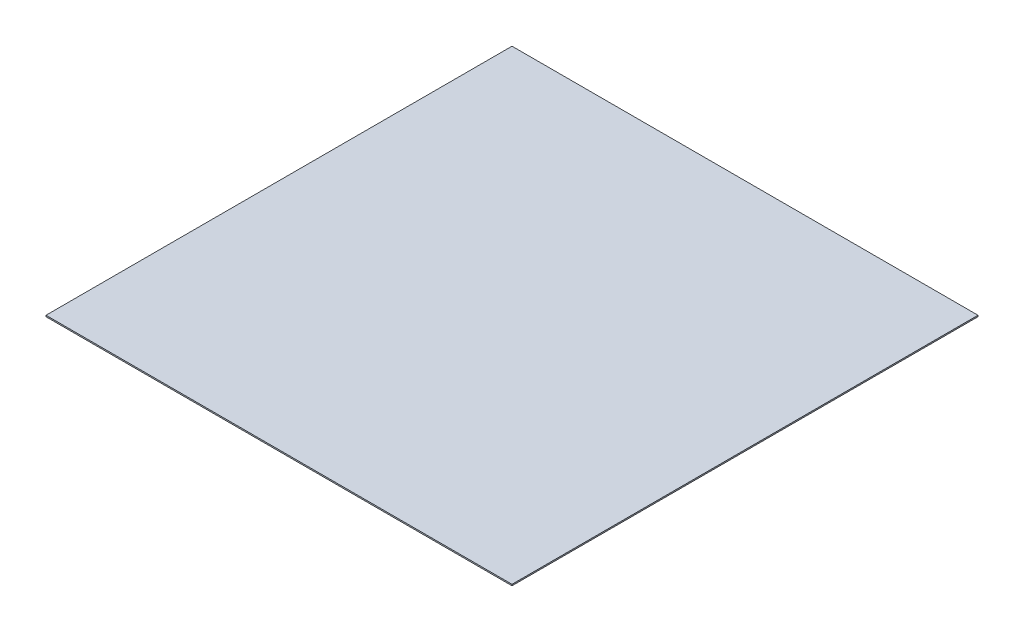
SolidWorks part; units mm, degrees
ref_plane "Front Plane" through (0, 0, 0) normal (0, 0, 1) x (1, 0, 0)
ref_plane "Top Plane" through (0, 0, 0) normal (0, 1, 0) x (1, 0, 0)
ref_plane "Right Plane" through (0, 0, 0) normal (1, 0, 0) x (0, 0, -1)
sketch "Sketch1" plane through (0, 0, 0) normal (0, 1, 0) x (1, 0, 0)
  line L1 (-1750, -1750) -> (1750, -1750)
  line L2 (-1750, -1750) -> (-1750, 1750)
  line L3 (-1750, 1750) -> (1750, 1750)
  line L4 (1750, -1750) -> (1750, 1750)
  line L5 (-1750, -1750) -> (1750, 1750) construction
  line L6 (-1750, 1750) -> (1750, -1750) construction
  point P0 (0, 0)
  dimension "D1" = 3500
  dimension "D2" = 3500
extrude "Boss-Extrude1" add sketch "Sketch1" along normal blind 10
